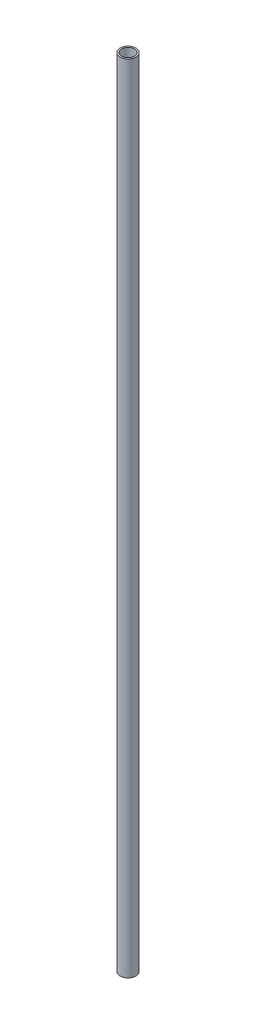
SolidWorks part; units mm, degrees
ref_plane "前视基准面" through (0, 0, 0) normal (0, 0, 1) x (1, 0, 0)
ref_plane "上视基准面" through (0, 0, 0) normal (0, 1, 0) x (1, 0, 0)
ref_plane "右视基准面" through (0, 0, 0) normal (1, 0, 0) x (0, 0, -1)
other "Configuration Table"
sketch "草图1" plane through (0, 0, 0) normal (0, 1, 0) x (1, 0, 0)
  circle A0 centre (0, 0) radius 2
  circle A1 centre (0, 0) radius 2.5
extrude "凸台-拉伸1" add sketch "草图1" along normal blind 250
